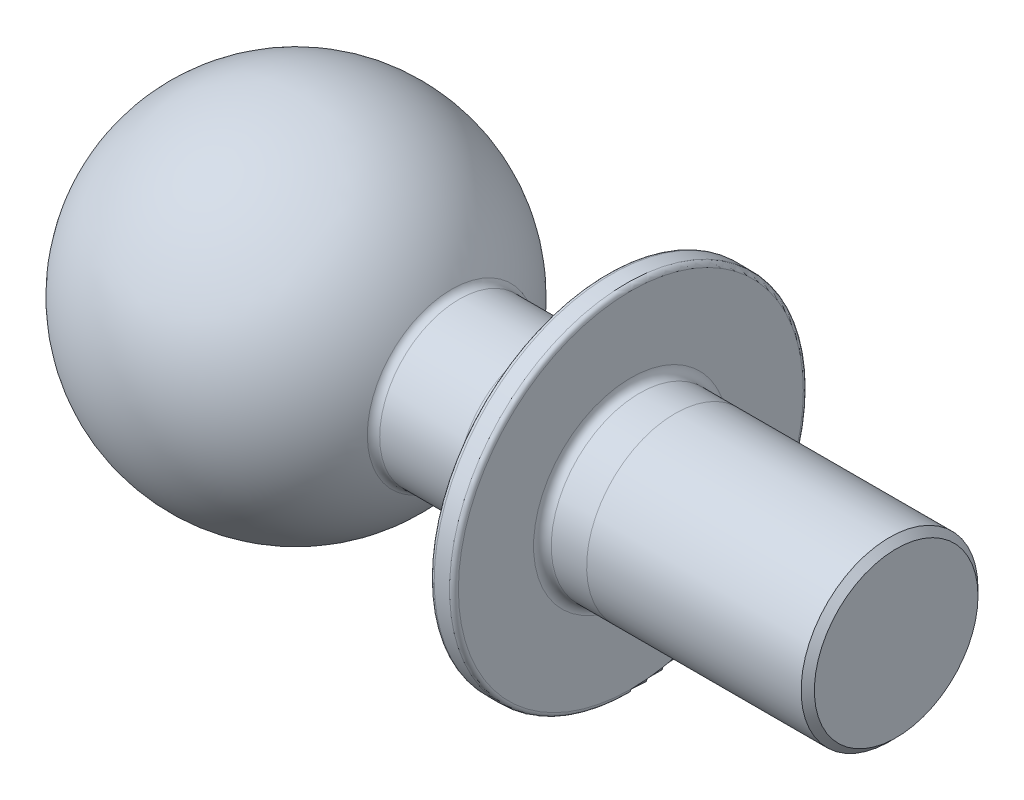
SolidWorks part; units mm, degrees
ref_plane "Front Plane" through (0, 0, 0) normal (0, 0, 1) x (1, 0, 0)
ref_plane "Top Plane" through (0, 0, 0) normal (0, 1, 0) x (1, 0, 0)
ref_plane "Right Plane" through (0, 0, 0) normal (1, 0, 0) x (0, 0, -1)
sketch "Sketch1" plane through (0, 0, 0) normal (0, 0, 1) x (1, 0, 0)
  line L0 (0, 0) -> (0, 1)
  line L1 (0, 1) -> (-3, 1)
  line L2 (-3, 1) -> (-3, 2)
  line L3 (-3, 2) -> (-3.25, 2)
  line L4 (-3.25, 2) -> (-4, 0.9)
  line L5 (-4, 0.9) -> (-5, 0.9)
  line L6 (0, 0) -> (-5, 0)
  line L7 (-5, 0) -> (-8.5845, 0)
  line L8 (-8.5845, 0) -> (-8.5845, 0.875)
  line L9 (-5, 0.9) -> (-5, 0) construction
  line L10 (-8.5845, 0) -> (-8.5845, -0.875) construction
  arc A0 (-8.5845, 0.875) -> (-5, 0.9) centre (-6.7861, 0) cw
  circle A1 centre (-6.7861, 0) radius 2 construction
  point P12 (0, 0)
  dimension "D8" = 4
  dimension "D9" = 2
  dimension "D1" = 1
  dimension "D2" = 3
  dimension "D3" = 1
  dimension "D4" = 0.25
  dimension "D5" = 1
  dimension "D6" = 1
  dimension "D7" = 0.9
  dimension "D10" = 1.75
revolve "Revolve1" add sketch "Sketch1" angle 360 about L6
chamfer "Chamfer1" distance 0.075 angle 45 1 edges at (0, 0, -1)
fillet "Fillet1" radius 0.1 3 edges at (-5, 0, -0.9) (-4, 0, -0.9) (-3, 0, -1)
fillet "Fillet2" radius 0.05 2 edges at (-3, 0, -2) (-3.25, 0, -2)
sketch "Sketch2" plane through (0, 0, 0) normal (0, 0, 1) x (1, 0, 0)
  line L0 (-2.5, 2.6966) -> (-2.5, -2.6319)
  point P2 (-2.3496, -2.6319)
  dimension "D1" = 2.5
split line "Split Line1"
sketch "Sketch3" plane through (-8.5845, 0, 0) normal (-1, 0, 0) x (0, 0, 1)
  line L1 (0, 0.664) -> (-0.575, 0.332)
  line L2 (-0.575, 0.332) -> (-0.575, -0.332)
  line L3 (-0.575, -0.332) -> (0, -0.664)
  line L4 (0, -0.664) -> (0.575, -0.332)
  line L5 (0.575, -0.332) -> (0.575, 0.332)
  line L6 (0.575, 0.332) -> (0, 0.664)
  circle A1 centre (0, 0) radius 0.575
  dimension "D2" = 1.15
extrude "Cut-Extrude1" cut sketch "Sketch3" against normal blind 1 contours L6 L1 L2 L3 L4 L5
fillet "Fillet3" radius 0.05 18 edges at (-7.5845, 0, -0.575) (-7.5845, 0.498, -0.2875) (-7.5845, 0.498, 0.2875) (-7.5845, -0.498, 0.2875) (-7.5845, -0.498, -0.2875) (-7.5845, 0, 0.575) (-8.0845, 0.332, 0.575) (-8.0845, 0.664, 0) (-8.0845, 0.332, -0.575) (-8.0845, -0.664, 0) (-8.0845, -0.332, 0.575) (-8.0845, -0.332, -0.575) (-8.5845, 0.498, 0.2875) (-8.5845, 0.498, -0.2875) (-8.5845, 0, -0.575) (-8.5845, -0.498, 0.2875) (-8.5845, 0, 0.575) (-8.5845, -0.498, -0.2875)
